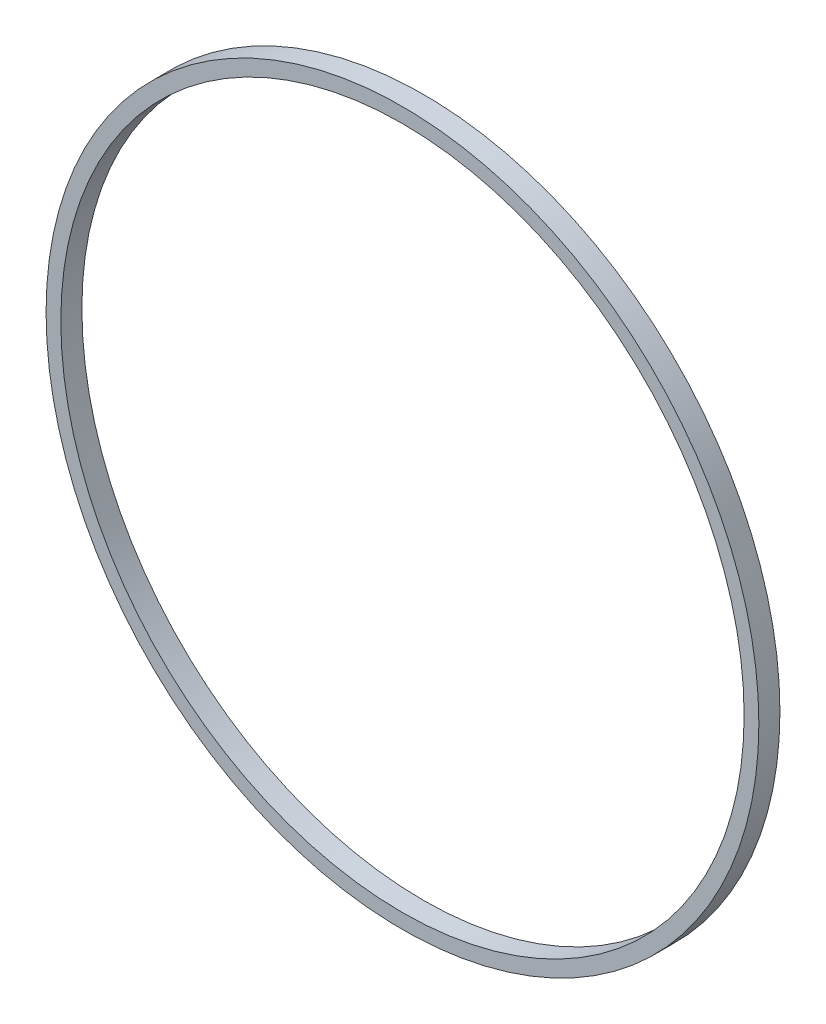
SolidWorks part; units mm, degrees
ref_plane "정면" through (0, 0, 0) normal (0, 0, 1) x (1, 0, 0)
ref_plane "윗면" through (0, 0, 0) normal (0, 1, 0) x (1, 0, 0)
ref_plane "우측면" through (0, 0, 0) normal (1, 0, 0) x (0, 0, -1)
sketch "스케치1" plane through (0, 0, 0) normal (0, 0, 1) x (1, 0, 0)
  circle A0 centre (0, 0) radius 81.1
  circle A1 centre (0, 0) radius 84.6
  dimension "D1" = 169.2
  dimension "D2" = 162.2
extrude "보스-돌출1" add sketch "스케치1" along normal blind 5
